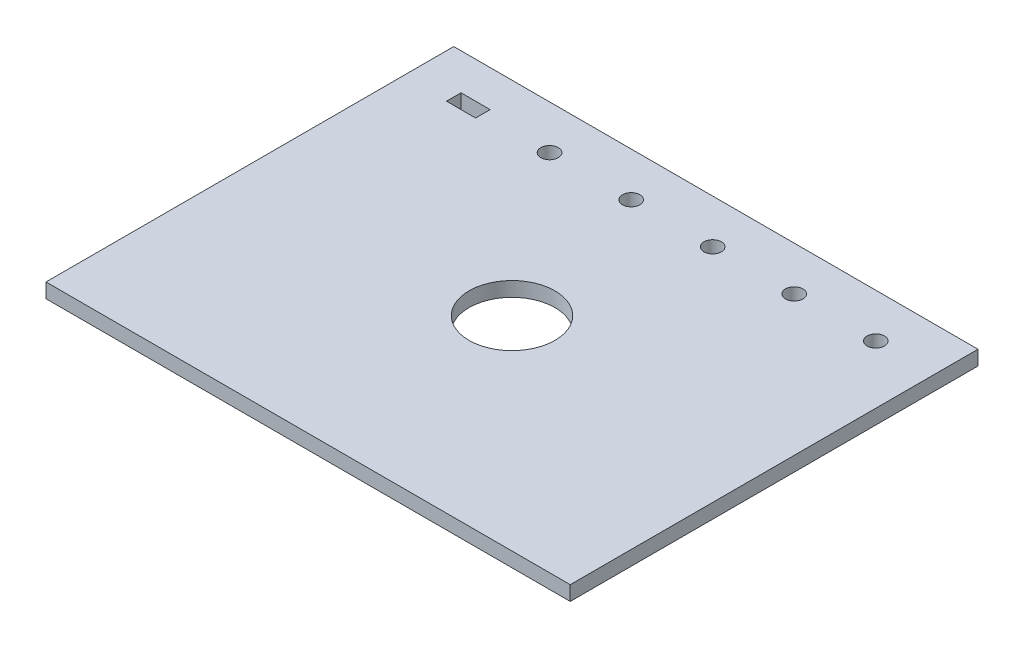
SolidWorks part; units mm, degrees
ref_plane "Ön Düzlem" through (0, 0, 0) normal (0, 0, 1) x (1, 0, 0)
ref_plane "Üst Düzlem" through (0, 0, 0) normal (0, 1, 0) x (1, 0, 0)
ref_plane "Sağ Düzlem" through (0, 0, 0) normal (1, 0, 0) x (0, 0, -1)
sketch "Çizim1" plane through (0, 0, 0) normal (0, 1, 0) x (1, 0, 0)
  line L1 (-90, -70) -> (90, -70)
  line L2 (-90, -70) -> (-90, 70)
  line L3 (-90, 70) -> (90, 70)
  line L4 (90, -70) -> (90, 70)
  line L5 (0, 70) -> (0, -70) construction
  line L6 (-90, 0) -> (90, 0) construction
  line L7 (-65, 52.5) -> (-75, 52.5)
  line L8 (-65, 52.5) -> (-65, 57.5)
  line L9 (-65, 57.5) -> (-75, 57.5)
  line L10 (-75, 52.5) -> (-75, 57.5)
  line L11 (-70, 57.5) -> (-70, 52.5) construction
  line L12 (-65, 55) -> (-75, 55) construction
  circle A0 centre (0, 0) radius 14.75
  circle A1 centre (70, 54.8951) radius 3
  circle A2 centre (42, 54.8951) radius 3
  circle A3 centre (14, 54.8951) radius 3
  circle A4 centre (-14, 54.8951) radius 3
  circle A5 centre (-42, 54.8951) radius 3
  point P0 (0, 0)
  point P16 (-70, 55)
  dimension "D3" = 29.5
  dimension "D4" = 6
  dimension "D5" = 6
  dimension "D6" = 6
  dimension "D7" = 6
  dimension "D8" = 6
  dimension "D11" = 28
  dimension "D12" = 28
  dimension "D13" = 28
  dimension "D14" = 28
  dimension "D15" = 28
  dimension "D17" = 15
  dimension "D1" = 180
  dimension "D2" = 140
  dimension "D9" = 10
  dimension "D10" = 5
  dimension "D16" = 20
extrude "Yükseklik-Ekstrüzyon1" add sketch "Çizim1" along normal blind 5
